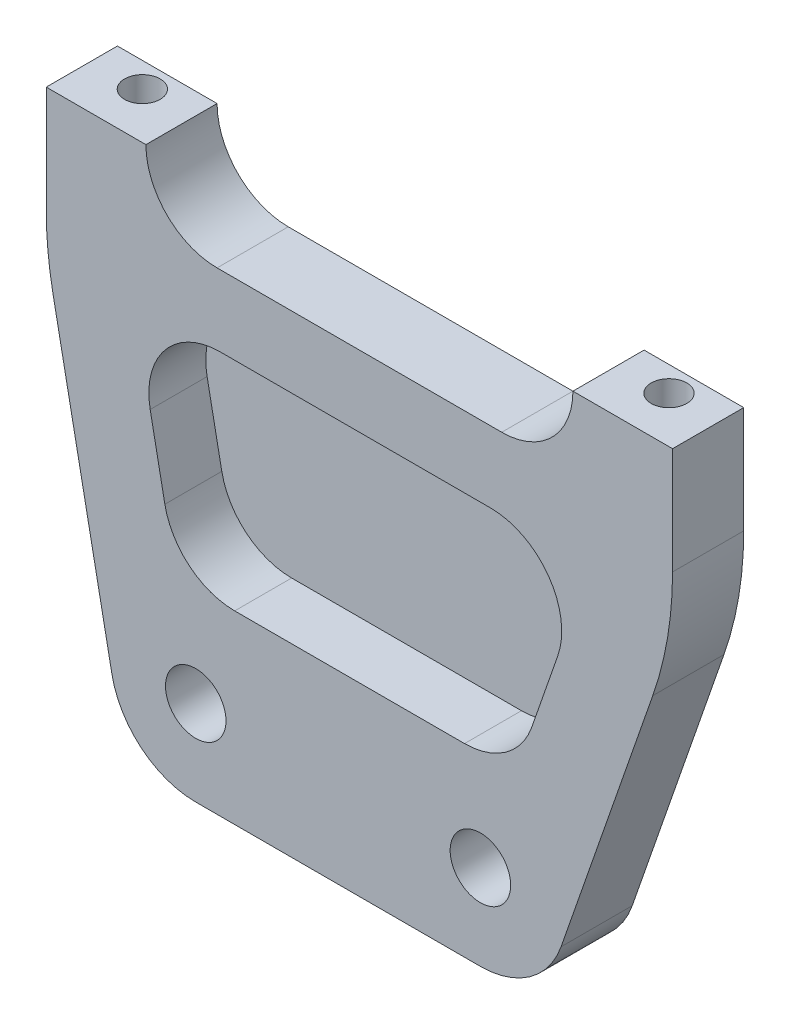
SolidWorks part; units mm, degrees
ref_plane "Front Plane" through (0, 0, 0) normal (0, 0, 1) x (1, 0, 0)
ref_plane "Top Plane" through (0, 0, 0) normal (0, 1, 0) x (1, 0, 0)
ref_plane "Right Plane" through (0, 0, 0) normal (1, 0, 0) x (0, 0, -1)
sketch "Sketch1" plane through (0, 0, 0) normal (0, 0, 1) x (1, 0, 0)
  line L0 (-14, 89.6343) -> (-14, 64.5) construction
  line L1 (-31.0401, 17.5) -> (50.2928, 17.5) construction
  line L2 (60, 89.6343) -> (60, 64.5) construction
  line L3 (-21, 64.5) -> (-7, 64.5)
  line L4 (3, 54.5) -> (43, 54.5)
  line L5 (53, 64.5) -> (67, 64.5)
  line L6 (67, 64.5) -> (67, 49.5)
  line L7 (64.2186, 33.0561) -> (51.3325, -3.9465)
  line L8 (40, -12) -> (0, -12)
  line L9 (-11.7748, -2.3137) -> (-20.0618, 39.8594)
  line L10 (-21, 49.5) -> (-21, 64.5)
  line L11 (-6.4003, 32.5719) -> (-4.3371, 22.0719)
  line L12 (5.4753, 14) -> (37.7689, 14)
  line L13 (47.2127, 20.7112) -> (50.8693, 31.2112)
  line L14 (41.4256, 44.5) -> (3.412, 44.5)
  line L15 (3, 54.5) -> (3, 44.5) construction
  line L16 (0, 4) -> (0, 14) construction
  circle A0 centre (0, 0) radius 4
  circle A1 centre (40, 0) radius 4
  arc A2 (-7, 64.5) -> (3, 54.5) centre (3, 64.5) ccw
  arc A3 (43, 54.5) -> (53, 64.5) centre (43, 64.5) ccw
  arc A4 (51.3325, -3.9465) -> (40, -12) centre (40, 0) cw
  arc A5 (0, -12) -> (-11.7748, -2.3137) centre (0, 0) cw
  arc A6 (67, 49.5) -> (64.2186, 33.0561) centre (17, 49.5) cw
  arc A7 (-20.0618, 39.8594) -> (-21, 49.5) centre (29, 49.5) cw
  arc A8 (-4.3371, 22.0719) -> (5.4753, 14) centre (5.4753, 24) ccw
  arc A9 (37.7689, 14) -> (47.2127, 20.7112) centre (37.7689, 24) ccw
  arc A10 (50.8693, 31.2112) -> (41.4256, 44.5) centre (41.4256, 34.5) ccw
  arc A11 (-6.4003, 32.5719) -> (3.412, 44.5) centre (3.412, 34.5) cw
  dimension "D1" = 8
  dimension "D8" = 12
  dimension "D9" = 50
  dimension "D2" = 40
  dimension "D3" = 17.5
  dimension "D4" = 47
  dimension "D5" = 74
  dimension "D6" = 14
  dimension "D7" = 14
  dimension "D10" = 15
  dimension "D11" = 10
  dimension "D12" = 10
extrude "Boss-Extrude1" add sketch "Sketch1" along normal blind 12.7
sketch "Sketch2" plane through (0, 0, 0) normal (1, 0, 0) x (0, 0, -1)
  line L0 (-12.7, -3.9465) -> (-12.7, 33.0561) construction
  line L1 (-12.7, 17.5) -> (-10, 17.5)
  line L2 (-12.7, 17.5) -> (-12.7, -12)
  line L3 (-12.7, -12) -> (-10, -12)
  line L4 (-10, 17.5) -> (-10, -12)
  dimension "D1" = 2.7
extrude "Cut-Extrude1" cut sketch "Sketch2" against normal through all both and the other way through all
hole_wizard "M6x1.0 Tapped Hole1" positions "Sketch3" profile "Sketch4" tap size "M6x1.0" standard "ANSI Metric"
sketch "Sketch3" plane through (0, 64.5, 0) normal (0, 1, 0) x (1, 0, 0)
  line L0 (45.3683, -10) -> (58.8012, -10) construction
  point P0 (-14, -3.5)
  point P2 (60, -3.5)
  dimension "D1" = 6.5
sketch "Sketch4" plane through (-14, 64.5, 3.5) normal (1, 0, 0) x (0, 0, 1)
  line L0 (0, 0) -> (0, 16.5022)
  line L1 (0, 16.5022) -> (2.5, 15)
  line L2 (2.5, 15) -> (2.5, 0)
  line L5 (2.5, 0) -> (0, 0)
  line L10 (0, 16.5022) -> (-2.5, 15) construction
  line L11 (0, -6.35) -> (0, 107.95) construction
  dimension "Tap Drill Dia." = 5
  dimension "Tap Drill Depth" = 15
  dimension "Drill Angle" = 118
cosmetic thread "Hole Thread1" parameters "D1"=12, "D2"=6
cosmetic thread "Hole Thread2" parameters "D1"=12, "D2"=6
sketch "Sketch5" plane through (0, 0, 0) normal (0, 0, 1) x (1, 0, 0)
  line L4 (5.4753, 14) -> (37.7689, 14)
  line L5 (47.2127, 20.7112) -> (50.8693, 31.2112)
  line L6 (41.4256, 44.5) -> (3.412, 44.5)
  line L7 (-6.4003, 32.5719) -> (-4.3371, 22.0719)
  line L8 (5.4753, 14) -> (37.7689, 14)
  line L9 (47.2127, 20.7112) -> (50.8693, 31.2112)
  line L10 (41.4256, 44.5) -> (3.412, 44.5)
  line L11 (-6.4003, 32.5719) -> (-4.3371, 22.0719)
  arc A4 (-4.3371, 22.0719) -> (5.4753, 14) centre (5.4753, 24) ccw
  arc A5 (37.7689, 14) -> (47.2127, 20.7112) centre (37.7689, 24) ccw
  arc A6 (50.8693, 31.2112) -> (41.4256, 44.5) centre (41.4256, 34.5) ccw
  arc A7 (3.412, 44.5) -> (-6.4003, 32.5719) centre (3.412, 34.5) ccw
  arc A8 (-4.3371, 22.0719) -> (5.4753, 14) centre (5.4753, 24) ccw
  arc A9 (37.7689, 14) -> (47.2127, 20.7112) centre (37.7689, 24) ccw
  arc A10 (50.8693, 31.2112) -> (41.4256, 44.5) centre (41.4256, 34.5) ccw
  arc A11 (3.412, 44.5) -> (-6.4003, 32.5719) centre (3.412, 34.5) ccw
  dimension "D1" = 0
extrude "Boss-Extrude2" add sketch "Sketch5" along normal blind 2
hole_wizard "M10x1.5 Tapped Hole1" positions "Sketch6" profile "Sketch7" tap size "M10x1.5" standard "ANSI Metric" end condition up to next
sketch "Sketch6" plane through (0, 0, 10) normal (0, 0, 1) x (1, 0, 0)
  point P0 (0, 0)
  point P3 (40, 0)
sketch "Sketch7" plane through (0, 0, 10) normal (1, 0, 0) x (0, -1, 0)
  line L0 (0, 0) -> (0, 10)
  line L1 (0, 10) -> (4.25, 10)
  line L2 (4.25, 10) -> (4.25, 0)
  line L5 (4.25, 0) -> (0, 0)
  line L11 (0, -6.35) -> (0, 107.95) construction
  dimension "Thru Tap Drill Dia." = 8.5
  dimension "Thru Tap Drill Depth" = 10
cosmetic thread "Hole Thread3" parameters "D1"=0, "D2"=9.5
cosmetic thread "Hole Thread4" parameters "D1"=0, "D2"=9.5
sketch "Sketch8" plane through (0, 0, 0) normal (1, 0, 0) x (0, 0, -1)
  line L0 (0, 64.5) -> (-10, 64.5)
  line L1 (0, 64.5) -> (0, -12)
  line L2 (-10, 64.5) -> (-10, -12)
  line L3 (0, -12) -> (-10, -12)
  line L4 (-10, 17.5) -> (-10, -3.9465) construction
extrude "Cut-Extrude2" cut sketch "Sketch8" against normal through all both and the other way through all flip side to cut
